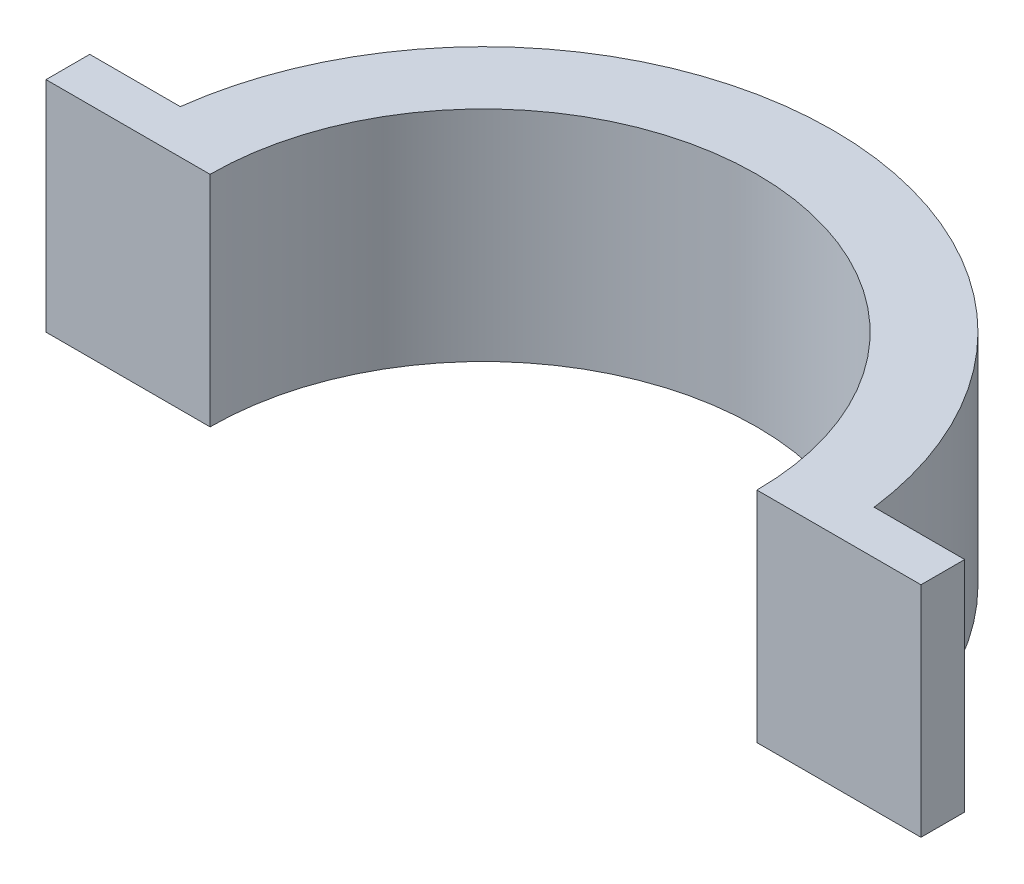
SolidWorks part; units mm, degrees
ref_plane "Front Plane" through (0, 0, 0) normal (0, 0, 1) x (1, 0, 0)
ref_plane "Top Plane" through (0, 0, 0) normal (0, 1, 0) x (1, 0, 0)
ref_plane "Right Plane" through (0, 0, 0) normal (1, 0, 0) x (0, 0, -1)
sketch "Sketch1" plane through (0, 0, 0) normal (0, 1, 0) x (1, 0, 0)
  line L0 (-12.5, 0) -> (12.5, 0)
  line L1 (12.5, 0) -> (20, 0)
  line L2 (-20, 0) -> (-20, 2)
  line L3 (19.2028, 2) -> (15.8603, 2)
  line L4 (-12.5, 0) -> (-20, 0)
  line L5 (-20, 2) -> (-19.2028, 2)
  line L6 (-19.2028, 2) -> (-15.8603, 2)
  line L7 (20, 0) -> (20, 2)
  line L8 (20, 2) -> (19.2028, 2)
  circle A0 centre (0, 0) radius 12.5
  circle A1 centre (0, 0) radius 15.9859
extrude "Boss-Extrude1" add sketch "Sketch1" along normal blind 10 contours A1 L6 L5 L2 L4 | L1 A1 L4 A0 | A1 L1 L7 L8 L3
